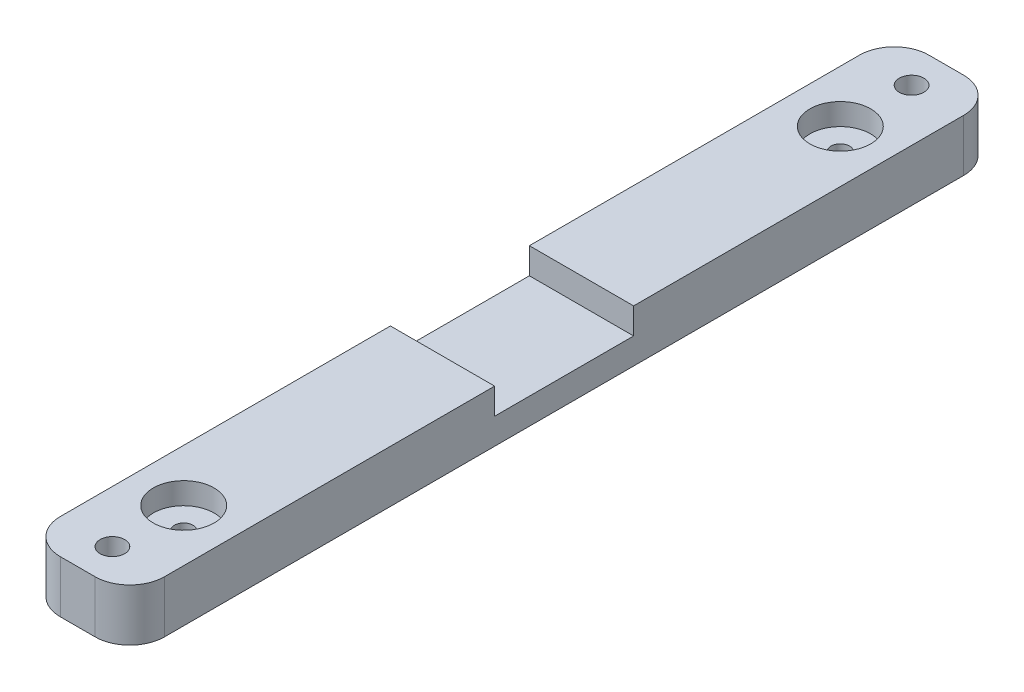
SolidWorks part; units mm, degrees
material "Delrin 2700 NC010, Low Viscosity Acetal Copolymer (SS)"
ref_plane "Front Plane" through (0, 0, 0) normal (0, 0, 1) x (1, 0, 0)
ref_plane "Top Plane" through (0, 0, 0) normal (0, 1, 0) x (1, 0, 0)
ref_plane "Right Plane" through (0, 0, 0) normal (1, 0, 0) x (0, 0, -1)
sketch "Sketch1" plane through (0, 0, 0) normal (0, 0, 1) x (1, 0, 0)
  line L1 (-9.525, -4.7625) -> (9.525, -4.7625)
  line L2 (-9.525, -4.7625) -> (-9.525, 4.7625)
  line L3 (-9.525, 4.7625) -> (9.525, 4.7625)
  line L4 (9.525, -4.7625) -> (9.525, 4.7625)
  line L5 (-9.525, -4.7625) -> (9.525, 4.7625) construction
  line L6 (-9.525, 4.7625) -> (9.525, -4.7625) construction
  point P0 (0, 0)
  dimension "D1" = 9.525
  dimension "D2" = 19.05
extrude "Boss-Extrude1" add sketch "Sketch1" along normal mid plane 158.75
sketch "Sketch2" plane through (0, 4.7625, 0) normal (0, 1, 0) x (1, 0, 0)
  line L0 (-9.525, -79.375) -> (-9.525, 79.375) construction
  line L1 (-9.525, -12.7) -> (9.525, -12.7)
  line L2 (-9.525, -12.7) -> (-9.525, 12.7)
  line L3 (-9.525, 12.7) -> (9.525, 12.7)
  line L4 (9.525, -12.7) -> (9.525, 12.7)
  line L5 (9.525, -79.375) -> (9.525, 79.375) construction
  line L6 (9.525, -79.375) -> (-9.525, -79.375) construction
  dimension "D1" = 66.675
  dimension "D2" = 25.4
extrude "Cut-Extrude1" cut sketch "Sketch2" against normal blind 4.7625
hole_wizard "M3 Clearance Hole1" positions "Sketch3" profile "Sketch4" hole size "M3" standard "ANSI Metric" end condition through all
sketch "Sketch3" plane through (0, 4.7625, 0) normal (0, 1, 0) x (1, 0, 0)
  line L2 (9.525, -79.375) -> (-9.525, -79.375) construction
  point P0 (0, -60)
  point P2 (0, 60)
  dimension "D1" = 120
  dimension "D2" = 19.375
sketch "Sketch4" plane through (0, 4.7625, 60) normal (1, 0, 0) x (0, 0, 1)
  line L0 (0, 0) -> (0, 9.525)
  line L1 (0, 9.525) -> (1.7, 9.525)
  line L2 (1.7, 9.525) -> (1.7, 0)
  line L5 (1.7, 0) -> (0, 0)
  line L11 (0, -6.35) -> (0, 107.95) construction
  dimension "Thru Hole Dia." = 3.4
  dimension "Thru Hole Depth" = 9.525
sketch "Sketch5" plane through (0, 4.7625, 0) normal (0, 1, 0) x (1, 0, 0)
  circle A0 centre (0, -60) radius 5.5563
  circle A1 centre (0, 60) radius 5.5563
  dimension "D1" = 11.1125
extrude "Cut-Extrude2" cut sketch "Sketch5" against normal blind 3.9688
hole_wizard "#8 Clearance Hole1" positions "Sketch6" profile "Sketch7" hole size "#8" standard "ANSI Inch" end condition through all
sketch "Sketch6" plane through (0, 4.7625, 0) normal (0, 1, 0) x (1, 0, 0)
  line L0 (9.525, -79.375) -> (-9.525, -79.375) construction
  line L1 (9.525, 79.375) -> (-9.525, 79.375) construction
  point P0 (0, -73.025)
  point P2 (0, 73.025)
  dimension "D1" = 6.35
  dimension "D2" = 6.35
sketch "Sketch7" plane through (0, 4.7625, 73.025) normal (1, 0, 0) x (0, 0, 1)
  line L0 (0, 0) -> (0, 9.525)
  line L1 (0, 9.525) -> (2.2479, 9.525)
  line L2 (2.2479, 9.525) -> (2.2479, 0)
  line L5 (2.2479, 0) -> (0, 0)
  line L11 (0, -6.35) -> (0, 107.95) construction
  dimension "Thru Hole Dia." = 4.4958
  dimension "Thru Hole Depth" = 9.525
fillet "Fillet1" radius 6.35 4 edges at (9.525, 0, -79.375) (-9.525, 0, -79.375) (9.525, 0, 79.375) (-9.525, 0, 79.375)
equation "\"D1@Sketch2\"=(6.25-\"D2@Sketch2\")/2"
equation "\"D1@Sketch3\"=120mm"
equation "\"D2@Sketch3\"=(6.25-\"D1@Sketch3\")/2"
equation "\"D2@Sketch6\"=\"D1@Sketch6\""
